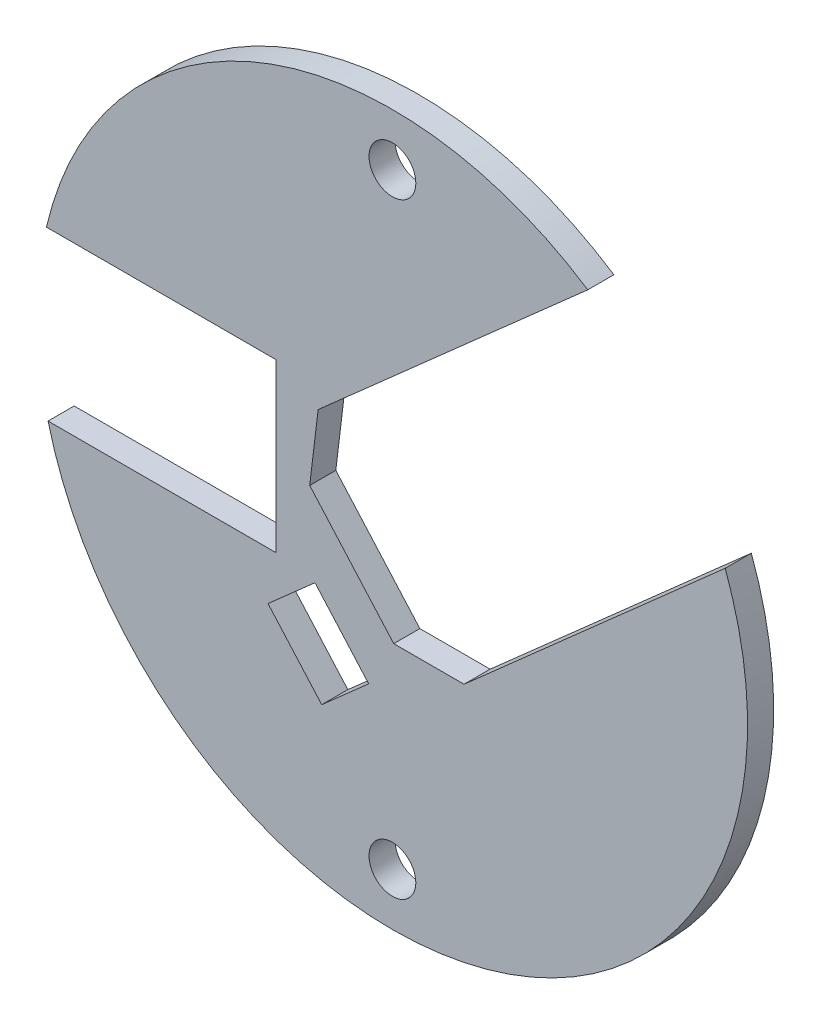
SolidWorks part; units mm, degrees
ref_plane "Front Plane" through (0, 0, 0) normal (0, 0, 1) x (1, 0, 0)
ref_plane "Top Plane" through (0, 0, 0) normal (0, 1, 0) x (1, 0, 0)
ref_plane "Right Plane" through (0, 0, 0) normal (1, 0, 0) x (0, 0, -1)
sketch "Sketch1" plane through (0, 0, 0) normal (0, 0, 1) x (1, 0, 0)
  line L0 (-4.5153, 3.5306) -> (-5.0276, -0.7207)
  line L1 (-5.0276, -0.7207) -> (0.0808, -6.4955)
  line L2 (4.3536, -6.4955) -> (0.0808, -6.4955)
  line L3 (-5.0276, -0.7207) -> (-2.4254, -3.6624) construction
  line L4 (-4.5153, 3.5306) -> (11.8761, 18.0302)
  line L5 (4.3536, -6.4955) -> (20.228, 7.5468)
  line L6 (-4.7083, -5.6818) -> (-1.4435, -9.3727)
  line L7 (-8.7203, -9.2308) -> (-2.4254, -3.6624) construction
  line L8 (-5.4555, -12.9216) -> (1.816, -6.4894) construction
  line L9 (-7.5621, -8.2062) -> (-4.2972, -11.897)
  line L10 (-7.5621, -8.2062) -> (-4.7083, -5.6818)
  line L11 (-1.4435, -9.3727) -> (-4.2972, -11.897)
  line L12 (-21.032, 4.8768) -> (-7.085, 4.8768)
  line L13 (-7.085, 4.8768) -> (-7.085, -5.2832)
  line L14 (-7.085, -5.2832) -> (-20.9336, -5.2832)
  arc A0 (20.8712, 5.5245) -> (20.8712, -5.5245) centre (0, 0) ccw construction
  circle A1 centre (0, 18.415) radius 1.4224 construction
  circle A2 centre (0, -18.415) radius 1.4224 construction
  circle A3 centre (0, 18.415) radius 1.4224
  circle A4 centre (0, -18.415) radius 1.4224
  circle A5 centre (0, 0) radius 21.59
  dimension "D1" = 3.048
  dimension "D2" = 3.81
extrude "Boss-Extrude1" add sketch "Sketch1" along normal blind 1.5875 contours L4 A5 L12 L13 L14 L5 L2 L1 L0 L6 L11 L9 L10 A3 A4
